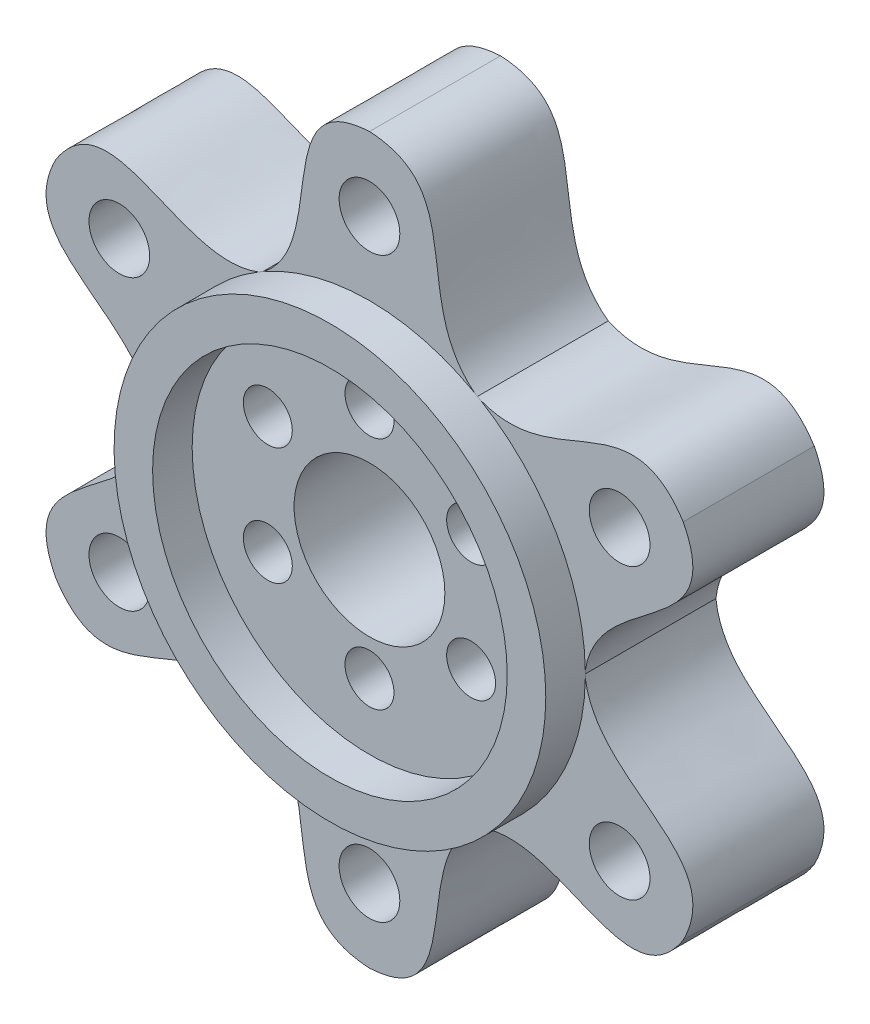
SolidWorks part; units mm, degrees
ref_plane "Front Plane" through (0, 0, 0) normal (0, 0, 1) x (1, 0, 0)
ref_plane "Top Plane" through (0, 0, 0) normal (0, 1, 0) x (1, 0, 0)
ref_plane "Right Plane" through (0, 0, 0) normal (1, 0, 0) x (0, 0, -1)
sketch "Sketch1" plane through (0, 0, 0) normal (0, 0, 1) x (1, 0, 0)
  line L0 (0, -2.035) -> (0, 2.035) construction
  line L1 (0, 0) -> (0, 46.99) construction
  circle A0 centre (0, 0) radius 9.779
  circle A1 centre (0, 0) radius 46.99
  circle A2 centre (0, 16.002) radius 3.175
  circle A3 centre (13.1849, 8.3897) radius 3.175
  circle A4 centre (13.1849, -6.8349) radius 3.175
  circle A5 centre (0, -14.4471) radius 3.175
  circle A6 centre (-13.1849, -6.8349) radius 3.175
  circle A7 centre (-13.1849, 8.3897) radius 3.175
  circle A8 centre (0, 37.465) radius 3.937
  circle A10 centre (32.4456, 18.7325) radius 3.937
  circle A11 centre (32.4456, -18.7325) radius 3.937
  circle A12 centre (0, -37.465) radius 3.937
  circle A13 centre (-32.4456, -18.7325) radius 3.937
  circle A14 centre (-32.4456, 18.7325) radius 3.937
  point P21 (0, 0.7774)
  point P36 (0, 0)
  dimension "D1" = 19.558
  dimension "D2" = 93.98
  dimension "D3" = 6.35
  dimension "D6" = 7.874
  dimension "D4" = 16.002
  dimension "D8" = 37.465
  dimension "D5" = 6
  dimension "D7" = 6
extrude "Boss-Extrude3" add sketch "Sketch1" along normal blind 17
sketch "Sketch2" plane through (0, 0, 17) normal (0, 0, 1) x (1, 0, 0)
  line L0 (0, -9.35) -> (0, 9.35) construction
  line L1 (-32.4456, 18.7325) -> (0, 37.465) construction
  line L2 (-16.2228, 28.0988) -> (-4.8895, 8.4689) construction
  line L3 (16.1678, 28.1305) -> (4.8344, 8.5004) construction
  line L6 (32.4456, -18.7325) -> (32.4456, 18.7325) construction
  line L7 (32.4456, 18.7325) -> (0, 37.465) construction
  line L8 (9.35, 0) -> (-9.35, 0) construction
  circle A0 centre (0, 0) radius 27.94 construction
  circle A1 centre (0, 0) radius 46.99 construction
  circle A2 centre (0, 0) radius 9.779 construction
  circle A3 centre (0, 0) radius 46.99
  spline S0 degree 3 poles (-13.97, 24.1967) (-4.8941, 30.8473) (-13.2477, 46.2899) (0, 46.99) knots 0 0 0 0 1 1 1 1
  spline S1 degree 3 poles (13.97, 24.1967) (4.8941, 30.8473) (13.2477, 46.2899) (0, 46.99) knots 0 0 0 0 1 1 1 1
  spline S2 degree 3 poles (-27.94, 0) (-29.1616, 11.1853) (-46.7121, 11.6721) (-40.6945, 23.495) knots 0 0 0 0 1 1 1 1
  spline S3 degree 3 poles (-13.97, 24.1967) (-24.2675, 19.6621) (-33.4643, 34.6178) (-40.6945, 23.495) knots 0 0 0 0 1 1 1 1
  spline S4 degree 3 poles (-13.97, -24.1967) (-24.2675, -19.6621) (-33.4643, -34.6178) (-40.6945, -23.495) knots 0 0 0 0 1 1 1 1
  spline S5 degree 3 poles (-27.94, 0) (-29.1616, -11.1853) (-46.7121, -11.6721) (-40.6945, -23.495) knots 0 0 0 0 1 1 1 1
  spline S6 degree 3 poles (13.97, -24.1967) (24.2675, -19.6621) (33.4643, -34.6178) (40.6945, -23.495) knots 0 0 0 0 1 1 1 1
  spline S7 degree 3 poles (27.94, 0) (29.1616, -11.1853) (46.7121, -11.6721) (40.6945, -23.495) knots 0 0 0 0 1 1 1 1
  spline S8 degree 3 poles (13.97, -24.1967) (4.8941, -30.8473) (13.2477, -46.2899) (0, -46.99) knots 0 0 0 0 1 1 1 1
  spline S9 degree 3 poles (-13.97, -24.1967) (-4.8941, -30.8473) (-13.2477, -46.2899) (0, -46.99) knots 0 0 0 0 1 1 1 1
  spline S10 degree 3 poles (27.94, 0) (29.1616, 11.1853) (46.7121, 11.6721) (40.6945, 23.495) knots 0 0 0 0 1 1 1 1
  spline S11 degree 3 poles (13.97, 24.1967) (24.2675, 19.6621) (33.4643, 34.6178) (40.6945, 23.495) knots 0 0 0 0 1 1 1 1
  point P5 (-16.2228, 28.0988)
  point P6 (16.1678, 28.1305)
  circle M8 centre (0, 0) radius 46.99
  dimension "D1" = 55.88
  dimension "D2" = 18.796
extrude "Cut-Extrude1" cut sketch "Sketch2" against normal blind 22.86 contours S1 S11 M8 | S5 S2 A3 | S10 S7 A3 | S6 S8 A3 | S9 S4 M8 | S3 S0 M8
sketch "Sketch4" plane through (0, 0, 17) normal (0, 0, 1) x (1, 0, 0)
  circle A0 centre (0, 0) radius 9.779 construction
  circle A1 centre (0, 0) radius 9.779 construction
  circle A2 centre (0, 0) radius 28
  circle A3 centre (0, 0) radius 23
  dimension "D1" = 56
  dimension "D2" = 46
extrude "Boss-Extrude4" add sketch "Sketch4" along normal blind 5.1308 contours A2 | A3
